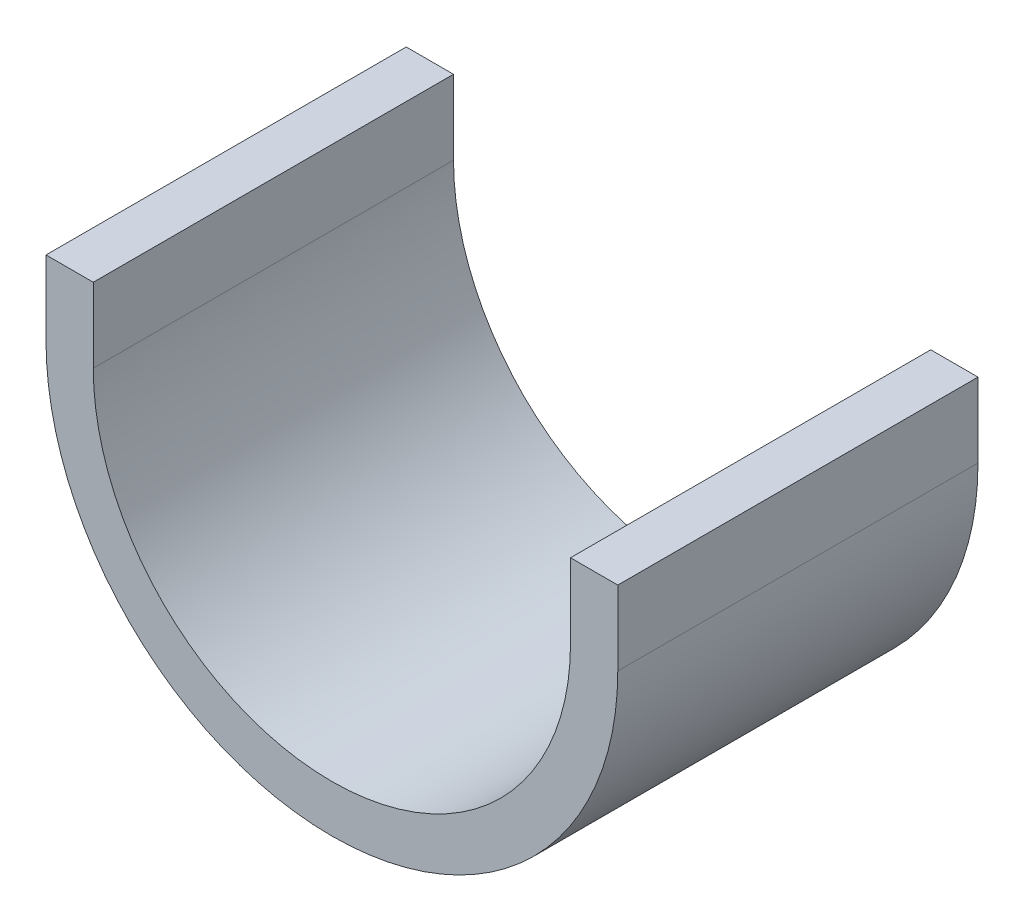
SolidWorks part; units mm, degrees
material "Silicon Rubber"
ref_plane "Front Plane" through (0, 0, 0) normal (0, 0, 1) x (1, 0, 0)
ref_plane "Top Plane" through (0, 0, 0) normal (0, 1, 0) x (1, 0, 0)
ref_plane "Right Plane" through (0, 0, 0) normal (1, 0, 0) x (0, 0, -1)
sketch "Sketch1" plane through (0, 0, 0) normal (0, 0, 1) x (1, 0, 0)
  line L0 (76.805, 20) -> (76.805, 0)
  line L2 (-76.805, 0) -> (-76.805, 20)
  line L3 (-76.805, 20) -> (-64.105, 20)
  line L4 (64.105, 0) -> (64.105, 20)
  line L5 (-64.105, 0) -> (-64.105, 20)
  line L7 (64.105, 20) -> (76.805, 20)
  arc A0 (-76.805, 0) -> (76.805, 0) centre (0, 0) ccw
  arc A1 (64.105, 0) -> (-64.105, 0) centre (0, 0) cw
  dimension "D1" = 12.7
extrude "Boss-Extrude1" add sketch "Sketch1" against normal blind 96.774
